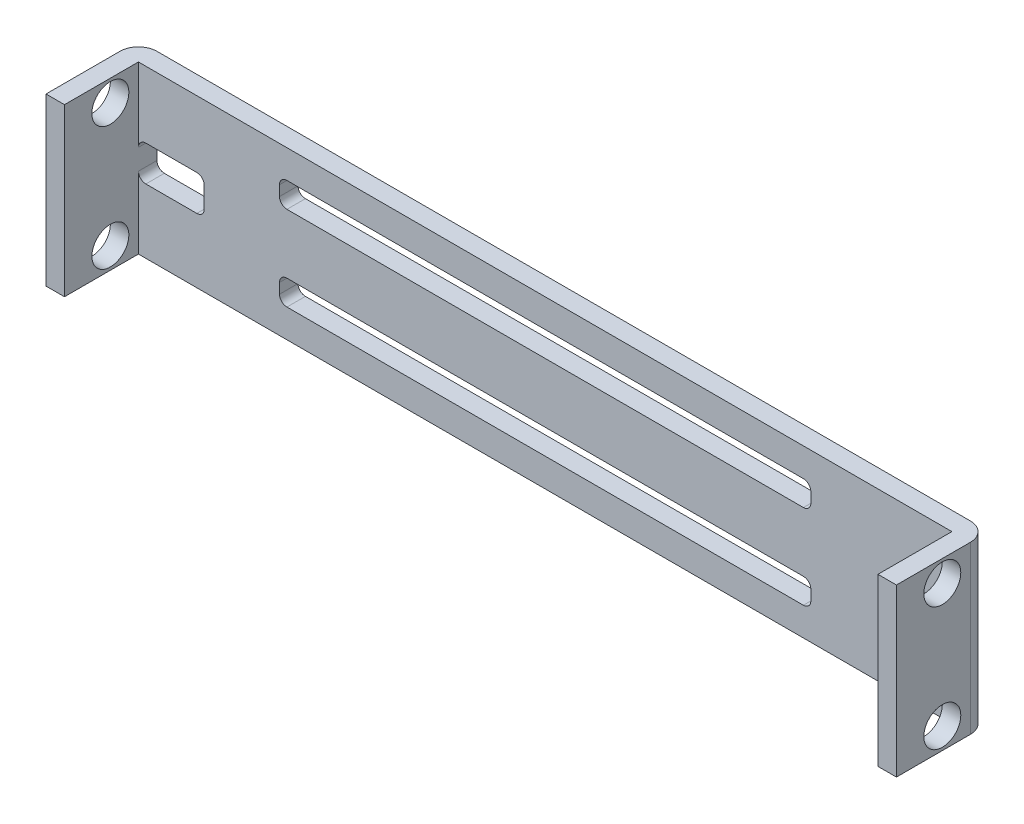
SolidWorks part; units mm, degrees
ref_plane "Front Plane" through (0, 0, 0) normal (0, 0, 1) x (1, 0, 0)
ref_plane "Top Plane" through (0, 0, 0) normal (0, 1, 0) x (1, 0, 0)
ref_plane "Right Plane" through (0, 0, 0) normal (1, 0, 0) x (0, 0, -1)
sketch "Sketch1" plane through (0, 0, 0) normal (0, 0, 1) x (1, 0, 0)
  line L1 (23, -4.5) -> (-23, -4.5)
  line L2 (23, -4.5) -> (23, 4.5)
  line L3 (23, 4.5) -> (-23, 4.5)
  line L4 (-23, -4.5) -> (-23, 4.5)
  line L5 (23, -4.5) -> (-23, 4.5) construction
  line L6 (23, 4.5) -> (-23, -4.5) construction
  point P0 (0, 0)
  dimension "D1" = 46
  dimension "D2" = 9
extrude "Boss-Extrude1" add sketch "Sketch1" along normal blind 1
sketch "Sketch2" plane through (0, 0, 1) normal (0, 0, 1) x (1, 0, 0)
  line L0 (-23, -4.5) -> (23, -4.5) construction
  line L1 (23, 4.5) -> (22, 4.5)
  line L2 (23, 4.5) -> (23, -4.5)
  line L3 (23, -4.5) -> (22, -4.5)
  line L4 (22, 4.5) -> (22, -4.5)
  line L6 (-23, 4.5) -> (-22, 4.5)
  line L7 (-23, 4.5) -> (-23, -4.5)
  line L8 (-23, -4.5) -> (-22, -4.5)
  line L9 (-22, 4.5) -> (-22, -4.5)
  dimension "D1" = 1
  dimension "D2" = 1
extrude "Boss-Extrude2" add sketch "Sketch2" along normal blind 4
sketch "Sketch3" plane through (23, 0, 0) normal (1, 0, 0) x (0, 0, -1)
  line L0 (0, 0) -> (-5, 0) construction
  line L1 (0, -4.5) -> (0, 4.5) construction
  line L2 (-5, -4.5) -> (-5, 4.5) construction
  circle A0 centre (-2.5196, 3.3427) radius 1
  circle A1 centre (-2.5196, -3.3427) radius 1
  dimension "D2" = 2
  dimension "D1" = 3.3427
extrude "Cut-Extrude1" cut sketch "Sketch3" against normal through all both and the other way through all
fillet "Fillet1" radius 1 2 edges at (-23, 0, 0) (23, 0, 0)
sketch "Sketch4" plane through (0, 0, 0) normal (0, 0, -1) x (-1, 0, 0)
  line L0 (0, 0) -> (-6.7572, 0) construction
  line L1 (-13.9692, 1.6123) -> (13.9692, 1.6123)
  line L2 (-14.3692, 2.0123) -> (-14.3692, 2.5647)
  line L3 (-13.9692, 2.9647) -> (13.9692, 2.9647)
  line L4 (14.3692, 2.0123) -> (14.3692, 2.5647)
  line L5 (-14.3692, 1.6123) -> (14.3692, 2.9647) construction
  line L6 (-14.3692, 2.9647) -> (14.3692, 1.6123) construction
  line L7 (-14.3692, -2.9647) -> (14.3692, -1.6123) construction
  line L8 (-14.3692, -1.6123) -> (14.3692, -2.9647) construction
  line L9 (14.3692, -2.0123) -> (14.3692, -2.5647)
  line L10 (-13.9692, -2.9647) -> (13.9692, -2.9647)
  line L11 (-14.3692, -2.0123) -> (-14.3692, -2.5647)
  line L12 (-13.9692, -1.6123) -> (13.9692, -1.6123)
  line L13 (-22, 4.5) -> (-22, -4.5) construction
  line L14 (-21.6, 0.9015) -> (-18.8405, 0.9015)
  line L15 (-22, 0.5015) -> (-22, -0.6153)
  line L16 (-21.6, -1.0153) -> (-18.8405, -1.0153)
  line L17 (-18.4405, 0.5015) -> (-18.4405, -0.6153)
  line L18 (0, 0) -> (0, 8.5085) construction
  line L19 (18.4405, 0.5015) -> (18.4405, -0.6153)
  line L20 (21.6, -1.0153) -> (18.8405, -1.0153)
  line L21 (22, 0.5015) -> (22, -0.6153)
  line L22 (21.6, 0.9015) -> (18.8405, 0.9015)
  arc A0 (13.9692, -2.9647) -> (14.3692, -2.5647) centre (13.9692, -2.5647) ccw
  arc A1 (-13.9692, -1.6123) -> (-14.3692, -2.0123) centre (-13.9692, -2.0123) ccw
  arc A2 (13.9692, -1.6123) -> (14.3692, -2.0123) centre (13.9692, -2.0123) cw
  arc A3 (-14.3692, -2.5647) -> (-13.9692, -2.9647) centre (-13.9692, -2.5647) ccw
  arc A4 (-14.3692, 2.5647) -> (-13.9692, 2.9647) centre (-13.9692, 2.5647) cw
  arc A5 (13.9692, 1.6123) -> (14.3692, 2.0123) centre (13.9692, 2.0123) ccw
  arc A6 (-13.9692, 1.6123) -> (-14.3692, 2.0123) centre (-13.9692, 2.0123) cw
  arc A7 (13.9692, 2.9647) -> (14.3692, 2.5647) centre (13.9692, 2.5647) cw
  arc A8 (-18.8405, 0.9015) -> (-18.4405, 0.5015) centre (-18.8405, 0.5015) cw
  arc A9 (-22, -0.6153) -> (-21.6, -1.0153) centre (-21.6, -0.6153) ccw
  arc A10 (-18.8405, -1.0153) -> (-18.4405, -0.6153) centre (-18.8405, -0.6153) ccw
  arc A11 (-21.6, 0.9015) -> (-22, 0.5015) centre (-21.6, 0.5015) ccw
  arc A12 (22, 0.5015) -> (21.6, 0.9015) centre (21.6, 0.5015) ccw
  arc A13 (21.6, -1.0153) -> (22, -0.6153) centre (21.6, -0.6153) ccw
  arc A14 (18.4405, -0.6153) -> (18.8405, -1.0153) centre (18.8405, -0.6153) ccw
  arc A15 (18.4405, 0.5015) -> (18.8405, 0.9015) centre (18.8405, 0.5015) cw
  point P0 (0, 2.2885)
  point P12 (0, -2.2885)
  point P50 (-18.4405, 0.9015)
  point P53 (-22, -1.0153)
  point P56 (-18.4405, -1.0153)
  point P59 (-22, 0.9015)
  point P62 (22, 0.9015)
  point P65 (22, -1.0153)
  point P68 (18.4405, -1.0153)
  point P71 (18.4405, 0.9015)
  dimension "D1" = 0.4
  dimension "D2" = 0.4
  dimension "D3" = 0.4
extrude "Cut-Extrude2" cut sketch "Sketch4" against normal blind 4
